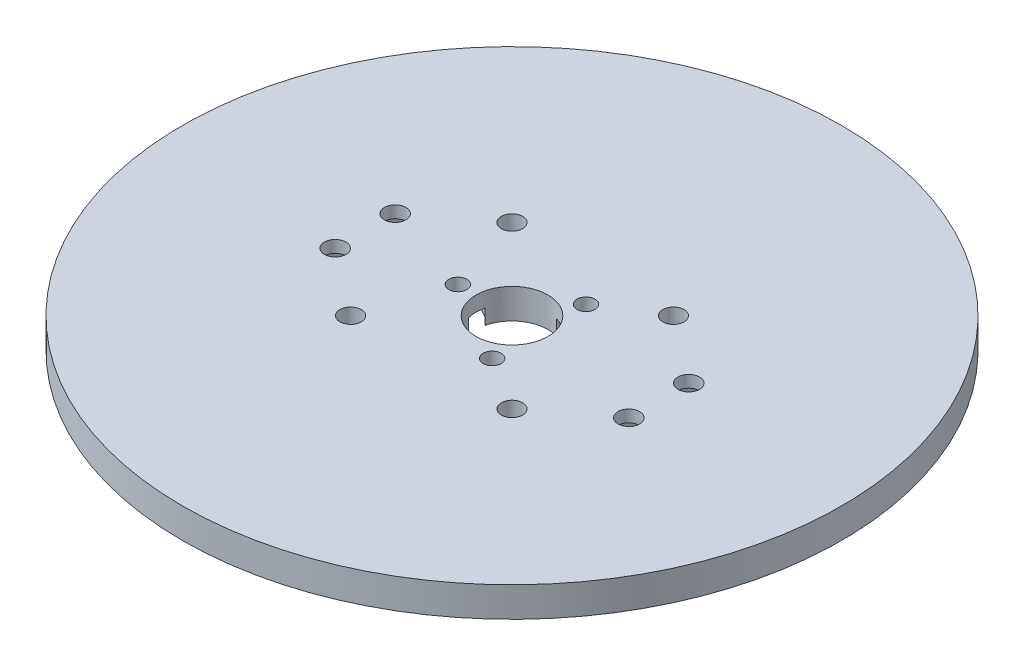
SolidWorks part; units mm, degrees
ref_plane "Front Plane" through (0, 0, 0) normal (0, 0, 1) x (1, 0, 0)
ref_plane "Top Plane" through (0, 0, 0) normal (0, 1, 0) x (1, 0, 0)
ref_plane "Right Plane" through (0, 0, 0) normal (1, 0, 0) x (0, 0, -1)
sketch "Sketch1" plane through (0, 0, 0) normal (0, 1, 0) x (1, 0, 0)
  circle A0 centre (0, 0) radius 55
  dimension "D1" = 110
extrude "Boss-Extrude1" add sketch "Sketch1" along normal blind 5
sketch "Sketch2" plane through (0, 5, 0) normal (0, 1, 0) x (1, 0, 0)
  line L1 (30.5, -29.5) -> (-30.5, -29.5)
  line L2 (30.5, -29.5) -> (30.5, 31.5)
  line L3 (30.5, 31.5) -> (-30.5, 31.5)
  line L4 (-30.5, -29.5) -> (-30.5, 31.5)
  circle A0 centre (0, 0) radius 6
  circle A1 centre (13.47, -13.47) radius 1.78
  circle A2 centre (-13.47, -13.47) radius 1.78
  circle A3 centre (-13.47, 13.47) radius 1.78
  circle A4 centre (13.47, 13.47) radius 1.78
  dimension "D1" = 12
  dimension "D2" = 61
  dimension "D5" = 31.5
  dimension "D6" = 3.56
  dimension "D8" = 17.03
  dimension "D11" = 13.47
  dimension "D7" = 13.47
  dimension "D3" = 61
  dimension "D4" = 30.5
  dimension "D9" = 2
  dimension "D10" = 2
extrude "Cut-Extrude1" cut sketch "Sketch2" along a picked direction on the side against the normal blind 5 contours A0 | A2 | A3 | A4 | A1
sketch "Sketch3" plane through (0, 5, 0) normal (0, 1, 0) x (1, 0, 0)
  line L0 (0, 0) -> (-9.035, 0)
  line L1 (-9.035, 0) -> (0, 0)
  line L2 (0, 0) -> (4.5175, 7.8245)
  line L3 (4.5175, 7.8245) -> (0, 0)
  line L4 (0, 0) -> (4.5175, -7.8245)
  circle A0 centre (0, 0) radius 9.035
  circle A1 centre (4.5175, -7.8245) radius 1.5
  circle A2 centre (-9.035, 0) radius 1.5
  circle A3 centre (4.5175, 7.8245) radius 1.5
  dimension "D1" = 18.07
  dimension "D4" = 3
  dimension "D5" = 3
  dimension "D6" = 3
  dimension "D2" = 120
  dimension "D3" = 120
extrude "Cut-Extrude2" cut sketch "Sketch3" against normal blind 5 contours A0 A2 L1 | A0 A2 | L1 A2 A0 | A0 A1 | A0 A1 L4 | L4 A1 A0 | A0 A3 | L3 A3 A0 | A0 A3 L3
sketch "Sketch5" plane through (0, 0, 0) normal (0, -1, 0) x (1, 0, 0)
  line L0 (4.4753, -11.5193) -> (7.6962, -9.7085)
  line L1 (7.7384, 9.6354) -> (4.5597, 11.5193)
  line L2 (4.5597, 11.5193) -> (1.3388, 9.7085)
  line L3 (1.3388, 9.7085) -> (1.2966, 6.0137)
  line L4 (1.2966, 6.0137) -> (4.4753, 4.1297)
  line L5 (4.4753, 4.1297) -> (7.6962, 5.9406)
  line L6 (7.6962, 5.9406) -> (7.7384, 9.6354)
  line L7 (7.6962, -9.7085) -> (7.7384, -6.0137)
  line L8 (7.7384, -6.0137) -> (4.5597, -4.1297)
  line L9 (4.5597, -4.1297) -> (1.3388, -5.9406)
  line L10 (1.3388, -5.9406) -> (1.2966, -9.6354)
  line L11 (1.2966, -9.6354) -> (4.4753, -11.5193)
  line L12 (-12.2137, 1.884) -> (-12.2559, -1.8108)
  line L13 (-12.2559, -1.8108) -> (-9.0772, -3.6948)
  line L14 (-9.0772, -3.6948) -> (-5.8563, -1.884)
  line L15 (-5.8563, -1.884) -> (-5.8141, 1.8108)
  line L16 (-5.8141, 1.8108) -> (-8.9928, 3.6948)
  line L17 (-8.9928, 3.6948) -> (-12.2137, 1.884)
  circle A0 centre (4.5175, 7.8245) radius 3.2 construction
  point P23 (0, 0)
  dimension "D2" = 6.4
  dimension "D1" = 3
extrude "Cut-Extrude5" cut sketch "Sketch5" against normal blind 2.5
sketch "Sketch6" plane through (0, 5, 0) normal (0, 1, 0) x (1, 0, 0)
  circle A0 centre (24.5, -5) radius 1.8
  circle A2 centre (-24.5, -5) radius 1.8
  circle A3 centre (-24.5, 5) radius 1.8
  circle A4 centre (24.5, 5) radius 1.8
  dimension "D1" = 3.6
  dimension "D2" = 24.5
  dimension "D3" = 5
  dimension "D4" = 2
  dimension "D5" = 2
extrude "Cut-Extrude6" cut sketch "Sketch6" against normal blind 10
sketch "Sketch7" plane through (0, 0, 0) normal (0, -1, 0) x (-1, 0, 0)
  line L0 (26.8094, -1) -> (22.1906, -1)
  line L1 (-29.1188, -5) -> (-26.8094, -9)
  line L2 (-26.8094, -9) -> (-22.1906, -9)
  line L3 (-22.1906, -9) -> (-19.8812, -5)
  line L4 (-19.8812, -5) -> (-22.1906, -1)
  line L5 (-22.1906, -1) -> (-26.8094, -1)
  line L6 (-26.8094, -1) -> (-29.1188, -5)
  line L7 (22.1906, -1) -> (19.8812, -5)
  line L8 (19.8812, -5) -> (22.1906, -9)
  line L9 (22.1906, -9) -> (26.8094, -9)
  line L10 (26.8094, -9) -> (29.1188, -5)
  line L11 (29.1188, -5) -> (26.8094, -1)
  line L12 (26.8094, 9) -> (22.1906, 9)
  line L13 (22.1906, 9) -> (19.8812, 5)
  line L14 (19.8812, 5) -> (22.1906, 1)
  line L15 (22.1906, 1) -> (26.8094, 1)
  line L16 (26.8094, 1) -> (29.1188, 5)
  line L17 (29.1188, 5) -> (26.8094, 9)
  line L18 (-22.1906, 9) -> (-26.8094, 9)
  line L19 (-26.8094, 9) -> (-29.1188, 5)
  line L20 (-29.1188, 5) -> (-26.8094, 1)
  line L21 (-26.8094, 1) -> (-22.1906, 1)
  line L22 (-22.1906, 1) -> (-19.8812, 5)
  line L23 (-19.8812, 5) -> (-22.1906, 9)
  circle A0 centre (-24.5, -5) radius 4 construction
  circle A1 centre (24.5, -5) radius 4 construction
  circle A2 centre (24.5, 5) radius 4 construction
  circle A3 centre (-24.5, 5) radius 4 construction
  dimension "D1" = 8
  dimension "D2" = 2
  dimension "D3" = 2
extrude "Cut-Extrude7" cut sketch "Sketch7" against normal blind 3
